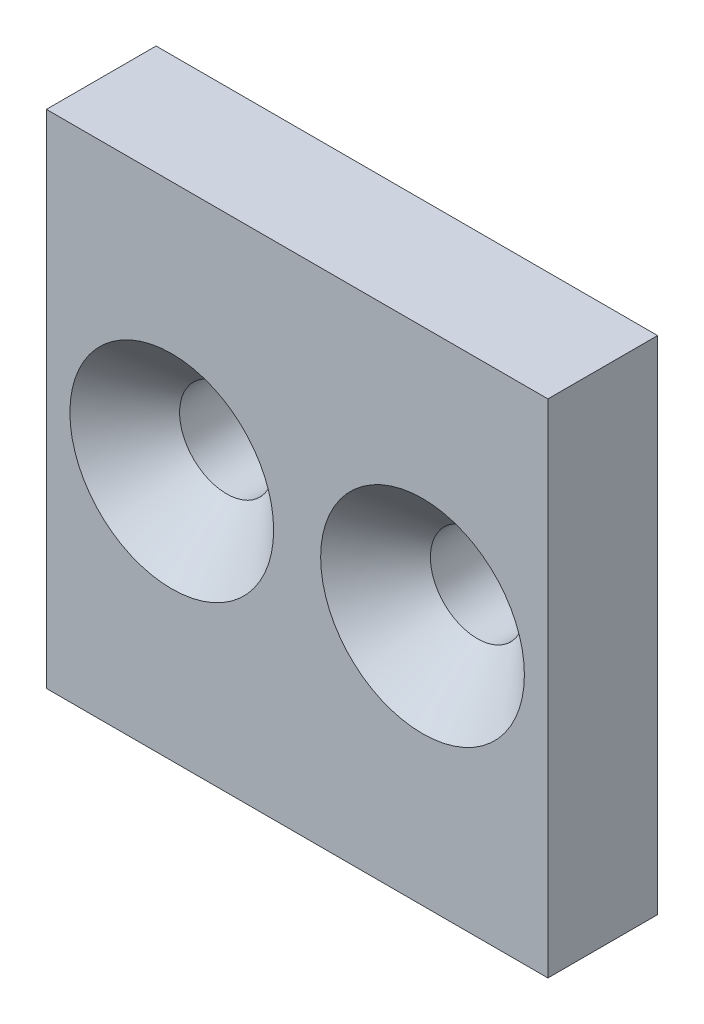
SolidWorks part; units mm, degrees
ref_plane "Front Plane" through (0, 0, 0) normal (0, 0, 1) x (1, 0, 0)
ref_plane "Top Plane" through (0, 0, 0) normal (0, 1, 0) x (1, 0, 0)
ref_plane "Right Plane" through (0, 0, 0) normal (1, 0, 0) x (0, 0, -1)
sketch "Sketch1" plane through (0, 0, 0) normal (0, 0, 1) x (1, 0, 0)
  line L1 (22.8802, 4.7559) -> (54.8802, 4.7559)
  line L2 (22.8802, 4.7559) -> (22.8802, -27.2441)
  line L3 (22.8802, -27.2441) -> (54.8802, -27.2441)
  line L4 (54.8802, 4.7559) -> (54.8802, -27.2441)
  dimension "D1" = 32
  dimension "D2" = 32
extrude "Boss-Extrude1" add sketch "Sketch1" along normal blind 7
sketch "Sketch10" plane through (0, 0, 0) normal (0, 0, 1) x (1, 0, 0)
  line L0 (22.8802, 4.7559) -> (22.8802, -27.2441) construction
  point P0 (30.8802, -11.2441)
  point P1 (46.8802, -11.2441)
  point P2 (22.8802, -11.2441)
  dimension "D1" = 8
  dimension "D2" = 16
hole_wizard "CSK for M6 Countersunk Flat Head Screw2" positions "Sketch15" profile "Sketch14" countersink size "M6" standard "ISO"
sketch "Sketch15" plane through (0, 0, 7) normal (0, 0, 1) x (1, 0, 0)
  point P0 (30.8802, -11.2441)
  point P3 (46.8802, -11.2441)
sketch "Sketch14" plane through (30.8802, -11.2441, 7) normal (1, 0, 0) x (0, -1, 0)
  line L0 (0, 0) -> (0, 24.8026)
  line L1 (0, 24.8026) -> (3, 23)
  line L2 (3, 23) -> (3, 3.5)
  line L3 (3, 3.5) -> (6.5, 0)
  line L5 (6.5, 0) -> (0, 0)
  line L6 (-3, 3.5) -> (-6.5, 0) construction
  line L10 (0, 24.8026) -> (-3, 23) construction
  line L11 (0, -6.35) -> (0, 107.95) construction
  dimension "Hole Dia." = 6
  dimension "Hole Depth" = 23
  dimension "Near C'Sink Dia." = 13
  dimension "Near C'Sink Angle" = 90
  dimension "Drill Angle" = 118
